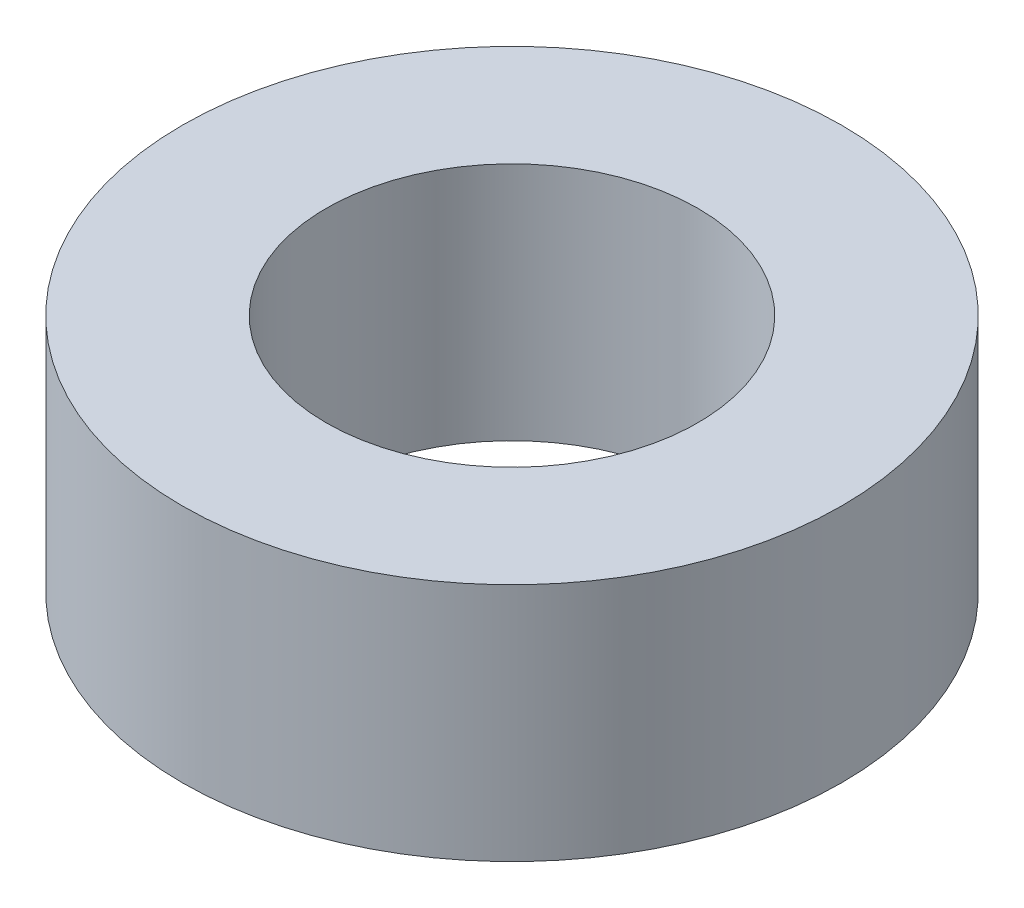
SolidWorks part; units mm, degrees
ref_plane "Front Plane" through (0, 0, 0) normal (0, 0, 1) x (1, 0, 0)
ref_plane "Top Plane" through (0, 0, 0) normal (0, 1, 0) x (1, 0, 0)
ref_plane "Right Plane" through (0, 0, 0) normal (1, 0, 0) x (0, 0, -1)
sketch "Sketch1" plane through (0, 0, 0) normal (0, 1, 0) x (1, 0, 0)
  circle A0 centre (0, 0) radius 1.55
  circle A1 centre (0, 0) radius 2.75
  dimension "D1" = 3.1
  dimension "D2" = 5.5
extrude "Boss-Extrude1" add sketch "Sketch1" along normal blind 2
